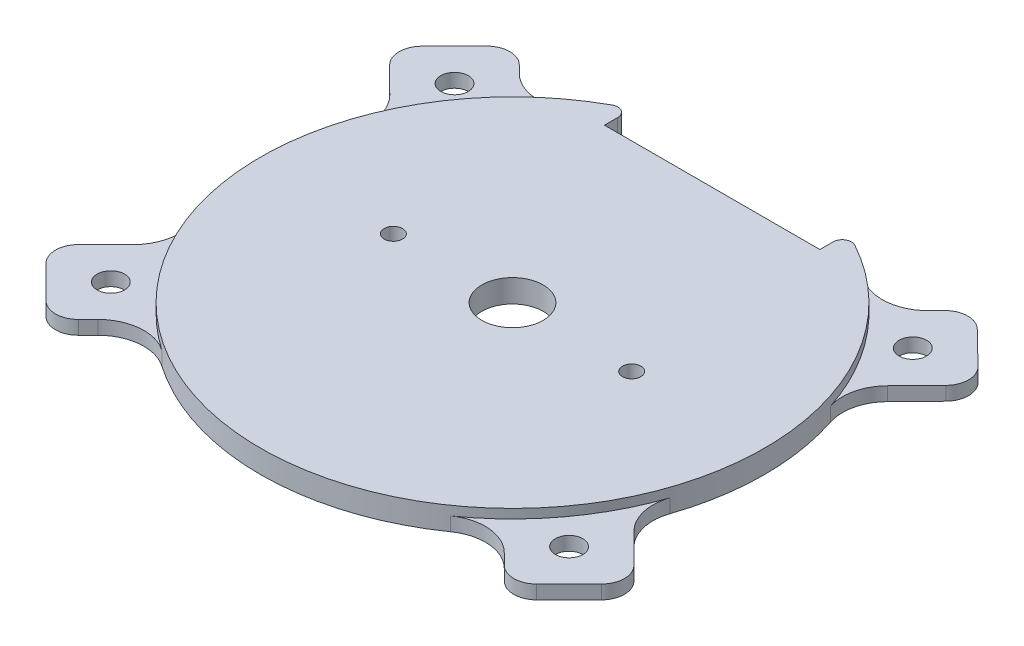
SolidWorks part; units mm, degrees
ref_plane "前视基准面" through (0, 0, 0) normal (0, 0, 1) x (1, 0, 0)
ref_plane "上视基准面" through (0, 0, 0) normal (0, 1, 0) x (1, 0, 0)
ref_plane "右视基准面" through (0, 0, 0) normal (1, 0, 0) x (0, 0, -1)
other "Configuration Table"
sketch "草图1" plane through (0, 0, 0) normal (0, 1, 0) x (1, 0, 0)
  circle A0 centre (0, 0) radius 55
  dimension "D1" = 110
extrude "凸台-拉伸1" add sketch "草图1" along normal blind 5
sketch "草图5" plane through (0, 5, 0) normal (0, 1, 0) x (1, 0, 0)
  line L0 (0, 0) -> (0, 49.5) construction
  line L1 (-23.5, 43.566) -> (23.5, 43.566)
  line L2 (-23.5, 43.566) -> (-23.5, 55.8089)
  line L3 (-23.5, 55.8089) -> (23.5, 55.8089)
  line L4 (23.5, 55.8089) -> (23.5, 43.566)
  dimension "D1" = 47
extrude "切除-拉伸2" cut sketch "草图5" against normal blind 30
fillet "圆角4" radius 2 1 edges at (-23.5, 2.5, -49.7268)
fillet "圆角5" radius 2 1 edges at (23.5, 2.5, -49.7268)
sketch "草图10" plane through (0, 3, 0) normal (0, 1, 0) x (1, 0, 0)
  line L0 (-49.7204, 37.0712) -> (62.5452, 37.0712) construction
  line L1 (-49.7204, 37.0712) -> (-49.7204, -35.3765) construction
  line L2 (-49.7204, -37.9288) -> (73.1761, -37.9288) construction
  circle A0 centre (-49.7204, 37.0712) radius 3
  circle A1 centre (50.2796, 37.0712) radius 3
  circle A2 centre (-49.7204, -37.9288) radius 3
  circle A3 centre (50.2796, -37.9288) radius 3
  dimension "D1" = 6
  dimension "D2" = 6
  dimension "D4" = 6
  dimension "D6" = 6
  dimension "D3" = 100
  dimension "D5" = 75
  dimension "D7" = 100
sketch "草图14" plane through (0, 3, 0) normal (0, 1, 0) x (1, 0, 0)
  line L0 (-49.8986, 23.1329) -> (-63.8625, 37.0448)
  line L1 (-63.8625, 37.0448) -> (-49.7468, 51.2133)
  line L2 (-49.7468, 51.2133) -> (-38.1286, 39.6385)
  line L3 (49.8119, -23.319) -> (64.4217, -37.9288)
  line L4 (-49.6324, -23.6986) -> (-63.8626, -37.9288)
  line L5 (-63.8626, -37.9288) -> (-49.7204, -52.0709)
  line L6 (-49.7204, -52.0709) -> (-37.6979, -40.0484)
  line L7 (38.4757, 39.3016) -> (50.1189, 51.2124)
  line L8 (50.1189, 51.2124) -> (64.4208, 37.2319)
  line L9 (64.4208, 37.2319) -> (50.1345, 22.6171)
  line L10 (64.4217, -37.9288) -> (50.2796, -52.0709)
  line L11 (50.2796, -52.0709) -> (37.9849, -39.7762)
  arc A0 (-26.4623, 48.2156) -> (26.4623, 48.2156) centre (0, 0) ccw construction
  arc A1 (-49.6324, -23.6986) -> (-37.6979, -40.0484) centre (0, 0) ccw
  arc A2 (-49.8986, 23.1329) -> (-38.1286, 39.6385) centre (0, 0) cw
  arc A3 (38.4757, 39.3016) -> (50.1345, 22.6171) centre (0, 0) cw
  arc A4 (49.8119, -23.319) -> (37.9849, -39.7762) centre (0, 0) cw
  dimension "D1" = 10
  dimension "D2" = 10
  dimension "D3" = 10
  dimension "D4" = 10
  dimension "D5" = 10
  dimension "D6" = 10
  dimension "D7" = 10
  dimension "D8" = 10
  dimension "D9" = 10
  dimension "D10" = 10
  dimension "D11" = 10
  dimension "D12" = 10
extrude "凸台-拉伸3" add sketch "草图14" against normal up to surface (3 mm away) up to face at (0, 0, -29.1602)
fillet "圆角7" radius 10 8 edges at (-49.6324, 1.5, 23.6986) (-37.6979, 1.5, 40.0484) (37.9849, 1.5, 39.7762) (49.8119, 1.5, 23.319) (50.1345, 1.5, -22.6171) (38.4757, 1.5, -39.3016) (-38.1286, 1.5, -39.6385) (-49.8986, 1.5, -23.1329)
fillet "圆角8" radius 5 8 edges at (-49.7468, 1.5, -51.2133) (-63.8625, 1.5, -37.0448) (-63.8626, 1.5, 37.9288) (-49.7204, 1.5, 52.0709) (50.2796, 1.5, 52.0709) (64.4217, 1.5, 37.9288) (64.4208, 1.5, -37.2319) (50.1189, 1.5, -51.2124)
extrude "切除-拉伸5" cut sketch "草图10" against normal up to surface (3 mm away) up to face at (0.1546, 0, -6.7887)
sketch "草图15" plane through (0, 5, 0) normal (0, 1, 0) x (1, 0, 0)
  circle A0 centre (0, 0) radius 6.7
  dimension "D1" = 13.4
extrude "切除-拉伸6" cut sketch "草图15" against normal blind 10
sketch "草图16" plane through (0, 5, 0) normal (0, 1, 0) x (1, 0, 0)
  line L0 (0, 0) -> (-35.2321, 0) construction
  circle A0 centre (-26, 0) radius 2
  circle A1 centre (26, 0) radius 2
  dimension "D1" = 4
  dimension "D2" = 4
  dimension "D3" = 52
  dimension "D4" = 26
extrude "切除-拉伸7" cut sketch "草图16" against normal blind 10
